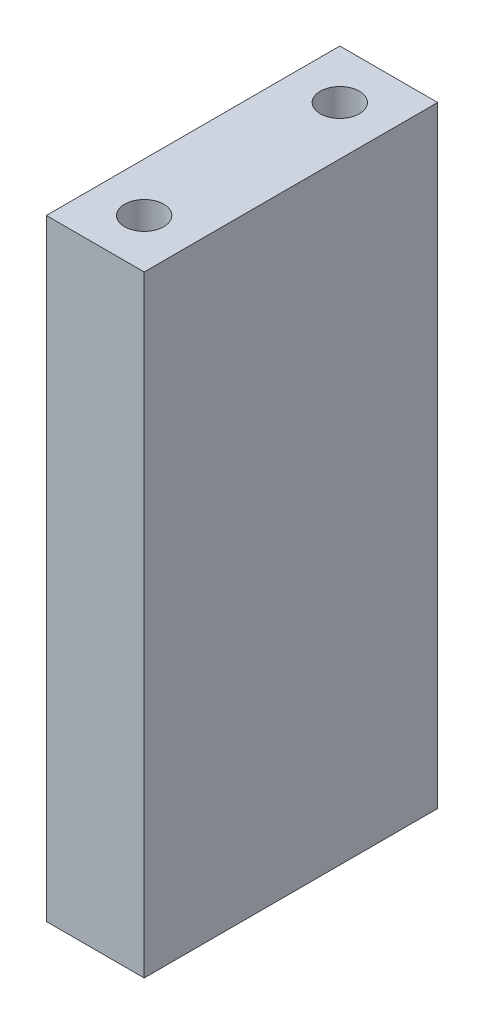
SolidWorks part; units mm, degrees
ref_plane "Alzado" through (0, 0, 0) normal (0, 0, 1) x (1, 0, 0)
ref_plane "Planta" through (0, 0, 0) normal (0, 1, 0) x (1, 0, 0)
ref_plane "Vista lateral" through (0, 0, 0) normal (1, 0, 0) x (0, 0, -1)
sketch "Croquis1" plane through (0, 0, 0) normal (1, 0, 0) x (0, 0, -1)
  line L1 (-30, 62.5) -> (30, 62.5)
  line L2 (-30, 62.5) -> (-30, -62.5)
  line L3 (-30, -62.5) -> (30, -62.5)
  line L4 (30, 62.5) -> (30, -62.5)
  line L5 (-30, 62.5) -> (30, -62.5) construction
  line L6 (-30, -62.5) -> (30, 62.5) construction
  point P0 (0, 0)
  dimension "D1" = 60
  dimension "D2" = 125
extrude "Saliente-Extruir1" add sketch "Croquis1" along normal blind 20
sketch "Croquis2" plane through (0, 62.5, 0) normal (0, 1, 0) x (1, 0, 0)
  line L0 (20, 30) -> (0, 30) construction
  line L1 (20, -30) -> (0, -30) construction
  line L2 (20, 30) -> (20, -30) construction
  circle A0 centre (10, 20) radius 4
  circle A1 centre (10, -20) radius 4
  dimension "D1" = 10
  dimension "D2" = 10
  dimension "D3" = 10
  dimension "D4" = 10
  dimension "D5" = 8
  dimension "D6" = 8
extrude "Cortar-Extruir1" cut sketch "Croquis2" against normal blind 25
sketch "Croquis3" plane through (0, -62.5, 0) normal (0, -1, 0) x (1, 0, 0)
  line L0 (0, 30) -> (0, -30) construction
  line L1 (20, -30) -> (0, -30) construction
  line L2 (20, 30) -> (20, -30) construction
  line L3 (20, 30) -> (0, 30) construction
  circle A0 centre (10, 20) radius 4
  circle A1 centre (10, -20) radius 4
  dimension "D1" = 10
  dimension "D2" = 8
  dimension "D3" = 10
  dimension "D4" = 10
  dimension "D5" = 10
  dimension "D6" = 8
extrude "Cortar-Extruir2" cut sketch "Croquis3" against normal blind 25
